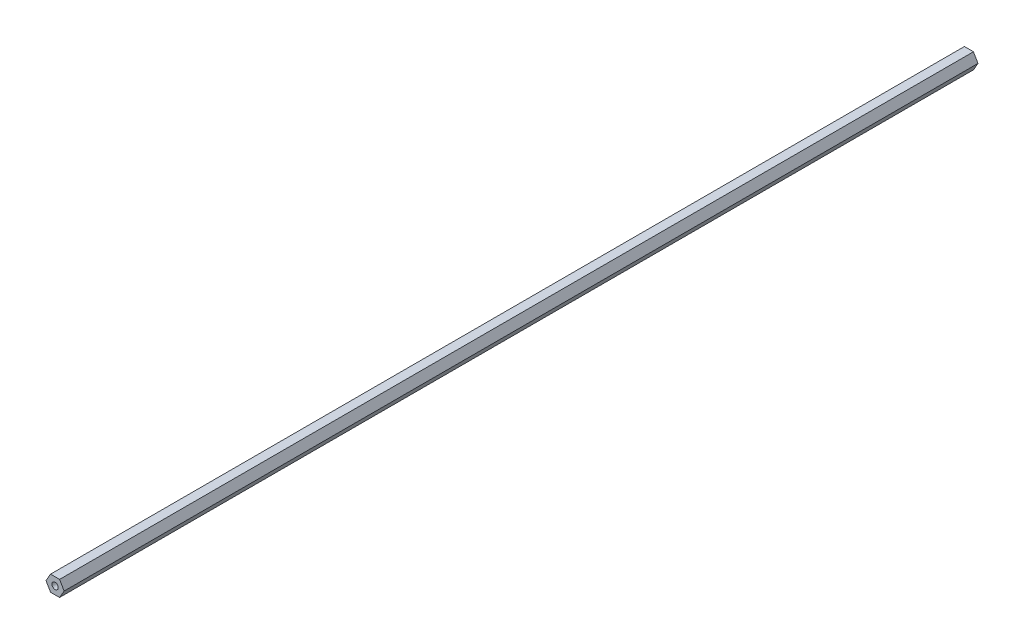
SolidWorks part; units mm, degrees
ref_plane "Front Plane" through (0, 0, 0) normal (0, 0, 1) x (1, 0, 0)
ref_plane "Top Plane" through (0, 0, 0) normal (0, 1, 0) x (1, 0, 0)
ref_plane "Right Plane" through (0, 0, 0) normal (1, 0, 0) x (0, 0, -1)
sketch "Sketch1" plane through (0, 0, 0) normal (0, 0, 1) x (1, 0, 0)
  line L1 (3.6662, -6.35) -> (7.3323, 0)
  line L2 (7.3323, 0) -> (3.6662, 6.35)
  line L3 (3.6662, 6.35) -> (-3.6662, 6.35)
  line L4 (-3.6662, 6.35) -> (-7.3323, 0)
  line L5 (-7.3323, 0) -> (-3.6662, -6.35)
  line L6 (-3.6662, -6.35) -> (3.6662, -6.35)
  circle A0 centre (0, 0) radius 6.35 construction
  circle A1 centre (0, 0) radius 2.5527
  dimension "D1" = 5.1054
  dimension "D2" = 12.7
extrude "Boss-Extrude1" add sketch "Sketch1" along normal blind 739.648
